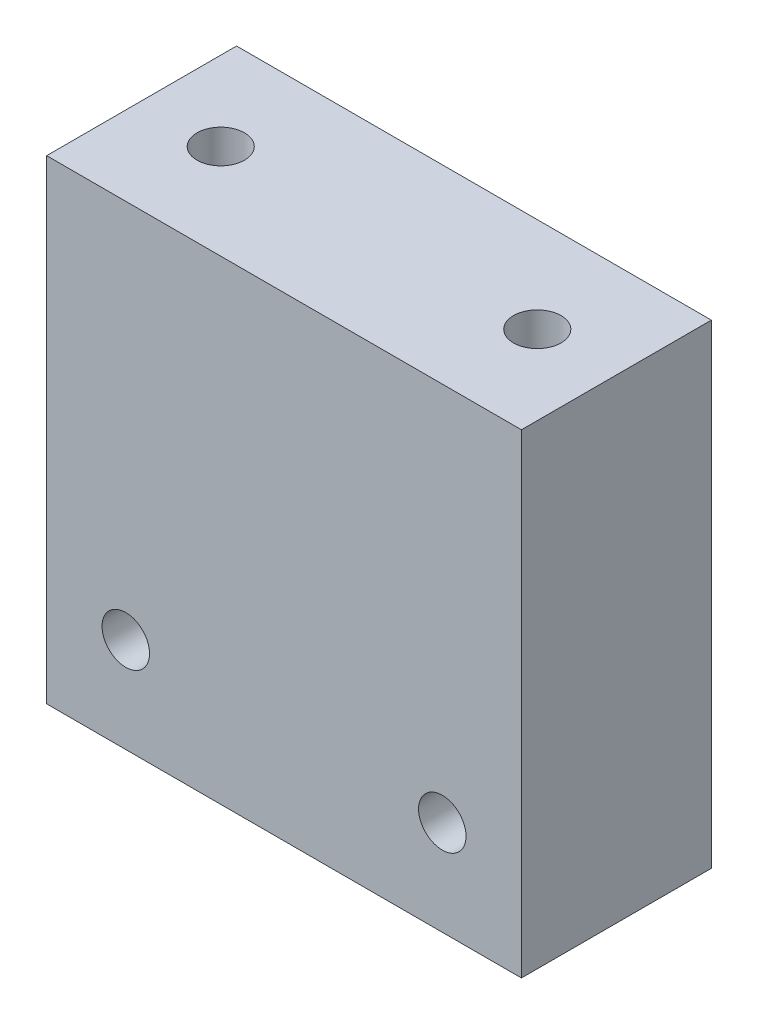
SolidWorks part; units mm, degrees
ref_plane "Front Plane" through (0, 0, 0) normal (0, 0, 1) x (1, 0, 0)
ref_plane "Top Plane" through (0, 0, 0) normal (0, 1, 0) x (1, 0, 0)
ref_plane "Right Plane" through (0, 0, 0) normal (1, 0, 0) x (0, 0, -1)
sketch "Sketch1" plane through (0, 0, 0) normal (0, 0, 1) x (1, 0, 0)
  line L1 (0, 0) -> (30, 0)
  line L2 (0, 0) -> (0, 30)
  line L3 (0, 30) -> (30, 30)
  line L4 (30, 0) -> (30, 30)
  dimension "D1" = 30
  dimension "D2" = 30
extrude "Boss-Extrude1" add sketch "Sketch1" along normal blind 12
sketch "Sketch2" plane through (0, 0, 12) normal (0, 0, 1) x (1, 0, 0)
  line L0 (0, 6) -> (30, 6) construction
  line L1 (0, 30) -> (0, 0) construction
  line L2 (30, 0) -> (30, 30) construction
  line L3 (0, 0) -> (30, 0) construction
  line L4 (15, 0) -> (15, 6) construction
  circle A0 centre (5, 6) radius 1.5
  circle A1 centre (25, 6) radius 1.5
  dimension "D2" = 3
  dimension "D1" = 6
  dimension "D3" = 20
extrude "Cut-Extrude1" cut sketch "Sketch2" against normal through all
sketch "Sketch3" plane through (0, 30, 0) normal (0, 1, 0) x (1, 0, 0)
  line L0 (0, -6) -> (30, -6) construction
  line L1 (0, -12) -> (0, 0) construction
  line L2 (30, -12) -> (30, 0) construction
  line L3 (15, -12) -> (15, 0) construction
  line L4 (30, -12) -> (0, -12) construction
  line L5 (30, 0) -> (0, 0) construction
  circle A0 centre (5, -6) radius 1.5
  circle A1 centre (25, -6) radius 1.5
  dimension "D1" = 3
  dimension "D2" = 20
extrude "Cut-Extrude2" cut sketch "Sketch3" against normal blind 5
